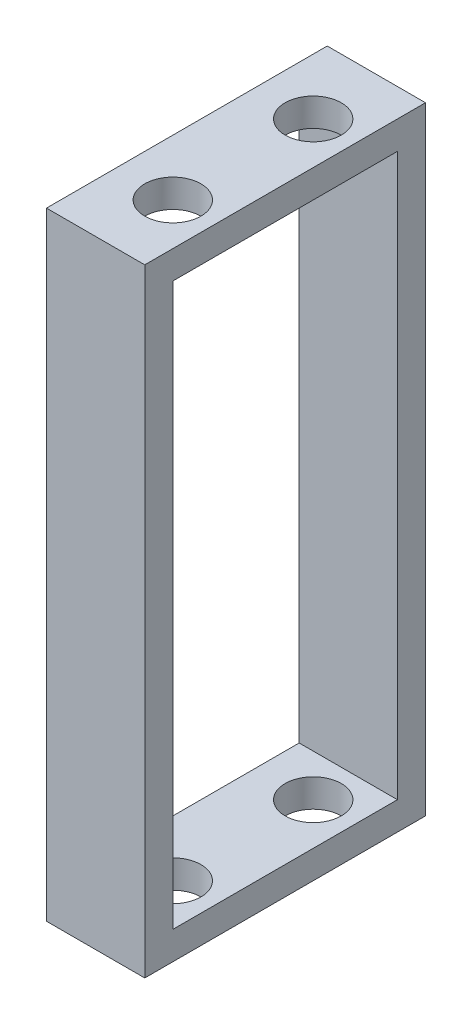
SolidWorks part; units mm, degrees
ref_plane "前视基准面" through (0, 0, 0) normal (0, 0, 1) x (1, 0, 0)
ref_plane "上视基准面" through (0, 0, 0) normal (0, 1, 0) x (1, 0, 0)
ref_plane "右视基准面" through (0, 0, 0) normal (1, 0, 0) x (0, 0, -1)
sketch "草图1" plane through (0, 0, 0) normal (0, 0, 1) x (1, 0, 0)
  line L0 (55, 0) -> (-55, 0) construction
  line L1 (0, 42) -> (0, 2)
  line L2 (0, 0) -> (7, 0)
  line L3 (7, 0) -> (7, 44)
  line L4 (7, 44) -> (0, 44)
  line L5 (0, -55) -> (0, 55) construction
  line L6 (0, 44) -> (0, 42)
  line L10 (0, 2) -> (0, 0)
  dimension "D1" = 7
extrude "凸台-拉伸1" add sketch "草图1" along normal mid plane 20
sketch "草图2" plane through (7, 0, 0) normal (1, 0, 0) x (0, 0, -1)
  line L0 (0, 55) -> (0, -55) construction
  line L1 (-8, 42) -> (8, 42)
  line L2 (-8, 42) -> (-8, 2)
  line L3 (-8, 2) -> (8, 2)
  line L4 (8, 42) -> (8, 2)
  line L5 (-8, 42) -> (8, 2) construction
  line L6 (-8, 2) -> (8, 42) construction
  point P0 (0, 22)
extrude "切除-拉伸1" cut sketch "草图2" against normal mid plane 20
sketch "草图3" plane through (0, 44, 0) normal (0, 1, 0) x (1, 0, 0)
  circle A0 centre (4, 5) radius 2
  circle A1 centre (4, -5) radius 2
extrude "切除-拉伸2" cut sketch "草图3" against normal blind 50
